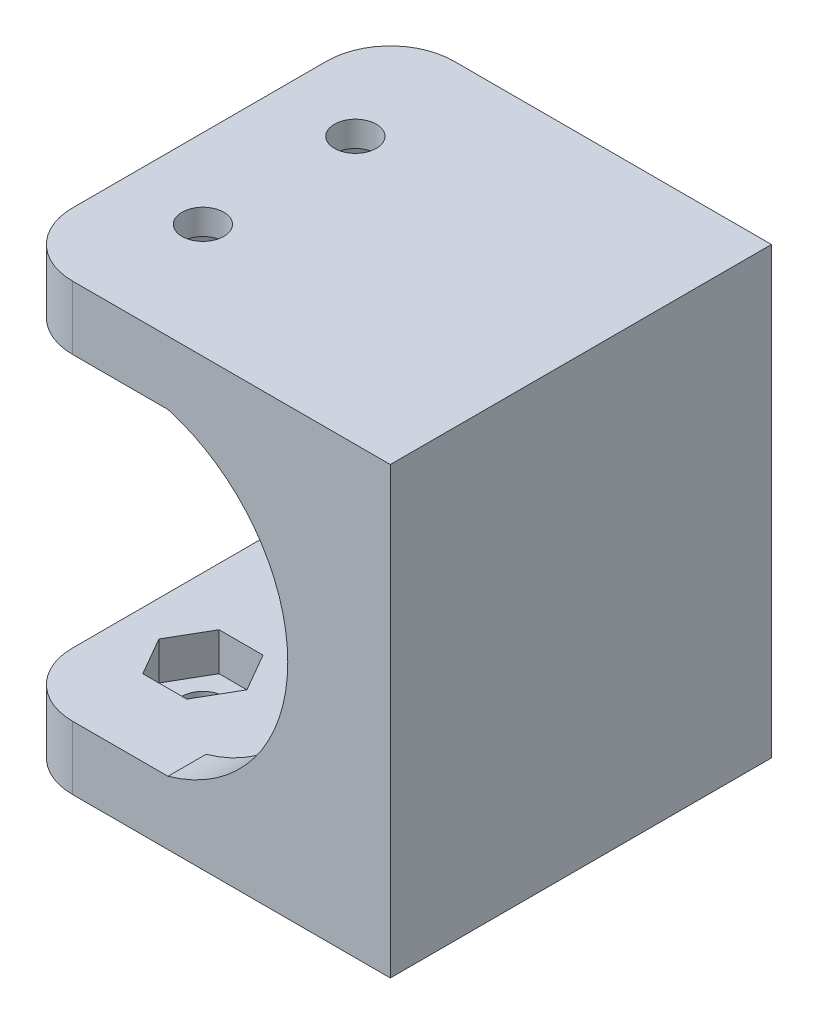
SolidWorks part; units mm, degrees
ref_plane "Спереди" through (0, 0, 0) normal (0, 0, 1) x (1, 0, 0)
ref_plane "Сверху" through (0, 0, 0) normal (0, 1, 0) x (1, 0, 0)
ref_plane "Справа" through (0, 0, 0) normal (1, 0, 0) x (0, 0, -1)
sketch "Эскиз1" plane through (0, 0, 0) normal (0, 0, 1) x (1, 0, 0)
  line L0 (0, 0) -> (30, 0)
  line L1 (30, 0) -> (30, 35)
  line L2 (30, 35) -> (0, 35)
  line L3 (0, 35) -> (0, 30)
  line L4 (0, 30) -> (25, 30)
  line L5 (25, 30) -> (25, 5)
  line L6 (25, 5) -> (0, 5)
  line L7 (0, 5) -> (0, 0)
  dimension "D1" = 35
  dimension "D2" = 5
  dimension "D3" = 5
  dimension "D4" = 5
  dimension "D5" = 30
extrude "Бобышка-Вытянуть1" add sketch "Эскиз1" along normal blind 30
sketch "Эскиз2" plane through (0, 0, 30) normal (0, 0, 1) x (1, 0, 0)
  line L0 (0, 30) -> (25, 30) construction
  line L1 (25, 5) -> (0, 5) construction
  line L2 (12.5, 30) -> (25, 30)
  line L3 (25, 30) -> (25, 5)
  line L4 (25, 5) -> (12.5, 5)
  arc A0 (12.5, 30) -> (12.5, 5) centre (8.9293, 17.5) cw
  dimension "D1" = 13
extrude "Бобышка-Вытянуть2" add sketch "Эскиз2" against normal blind 3
ref_plane "Плоскость1" through (0, 0, 15) normal (0, 0, 1) x (1, 0, 0)
mirror "Зеркальное отражение1" about plane through (0, 0, 15) normal (0, 0, 1) of "Бобышка-Вытянуть2"
sketch "Эскиз3" plane through (0, 5, 0) normal (0, 1, 0) x (1, 0, 0)
  line L0 (12.5, -3) -> (0, -3) construction
  line L1 (0, -30) -> (0, 0) construction
  line L2 (0, -3) -> (25, -27) construction
  line L3 (25, -15) -> (0, -15) construction
  line L4 (4.5179, -24) -> (2.7859, -21)
  line L5 (2.7859, -9) -> (4.5179, -12)
  line L6 (4.5179, -12) -> (7.9821, -12)
  line L7 (7.9821, -12) -> (9.7141, -9)
  line L8 (9.7141, -9) -> (7.9821, -6)
  line L9 (7.9821, -6) -> (4.5179, -6)
  line L10 (4.5179, -6) -> (2.7859, -9)
  line L17 (7.9821, -24) -> (4.5179, -24)
  line L18 (9.7141, -21) -> (7.9821, -24)
  line L19 (7.9821, -18) -> (9.7141, -21)
  line L20 (4.5179, -18) -> (7.9821, -18)
  line L21 (2.7859, -21) -> (4.5179, -18)
  circle A0 centre (6.25, -9) radius 3 construction
  point P10 (12.5, -15)
  dimension "D1" = 6
  dimension "D2" = 6
extrude "Вырез-Вытянуть1" cut sketch "Эскиз3" against normal blind 3
sketch "Эскиз4" plane through (0, 2, 0) normal (0, 1, 0) x (1, 0, 0)
  circle A0 centre (6.25, -21) radius 3.4641 construction
  circle A1 centre (6.25, -21) radius 1.65
  dimension "D1" = 3.3
extrude "Вырез-Вытянуть2" cut sketch "Эскиз4" against normal blind 17 and the other way blind 59
mirror "Зеркальное отражение2" about plane through (0, 0, 15) normal (0, 0, 1) of "Вырез-Вытянуть2"
sketch "Эскиз5" plane through (0, 30, 0) normal (0, -1, 0) x (1, 0, 0)
  line L1 (9.7141, 21) -> (7.9821, 24)
  line L2 (7.9821, 24) -> (4.5179, 24)
  line L3 (4.5179, 24) -> (2.7859, 21)
  line L4 (2.7859, 21) -> (4.5179, 18)
  line L5 (4.5179, 18) -> (7.9821, 18)
  line L6 (7.9821, 18) -> (9.7141, 21)
  circle A0 centre (6.25, 21) radius 3 construction
  dimension "D1" = 6
extrude "Вырез-Вытянуть3" cut sketch "Эскиз5" against normal blind 3
mirror "Зеркальное отражение3" about plane through (0, 0, 15) normal (0, 0, 1) of "Вырез-Вытянуть3"
fillet "Скругление1" radius 5 4 edges at (0, 32.5, 0) (0, 32.5, 30) (0, 2.5, 0) (0, 2.5, 30)
